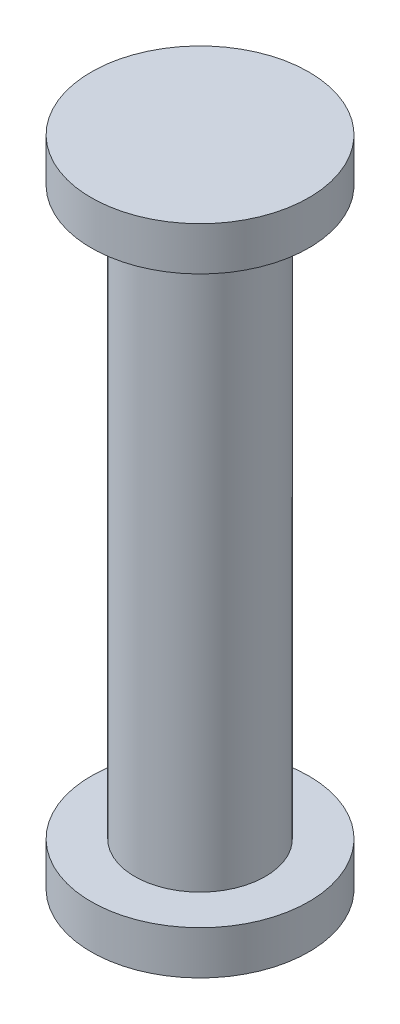
SolidWorks part; units mm, degrees
ref_plane "Front Plane" through (0, 0, 0) normal (0, 0, 1) x (1, 0, 0)
ref_plane "Top Plane" through (0, 0, 0) normal (0, 1, 0) x (1, 0, 0)
ref_plane "Right Plane" through (0, 0, 0) normal (1, 0, 0) x (0, 0, -1)
sketch "Sketch1" plane through (0, 0, 0) normal (0, 0, 1) x (1, 0, 0)
  line L0 (0, 0) -> (0, 15)
  line L1 (0, 15) -> (-2.5, 15)
  line L2 (-2.5, 15) -> (-2.5, 14)
  line L3 (-2.5, 14) -> (-1.5, 14)
  line L4 (-1.5, 14) -> (-1.5, 1)
  line L5 (-1.5, 1) -> (-2.5, 1)
  line L6 (-2.5, 1) -> (-2.5, 0)
  line L7 (-2.5, 0) -> (0, 0)
  dimension "D1" = 15
  dimension "D2" = 2.5
  dimension "D3" = 1
  dimension "D4" = 1.5
  dimension "D5" = 1
revolve "Revolve1" add sketch "Sketch1" angle 360 about L0
